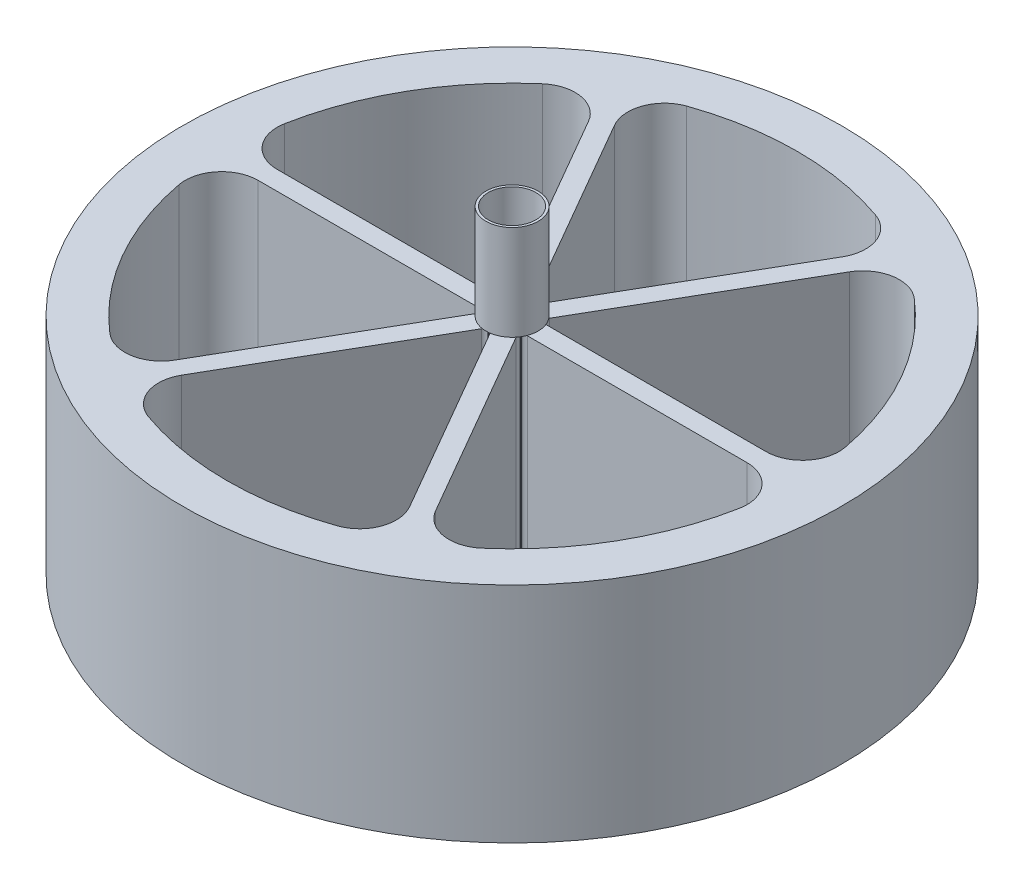
SolidWorks part; units mm, degrees
ref_plane "Front Plane" through (0, 0, 0) normal (0, 0, 1) x (1, 0, 0)
ref_plane "Top Plane" through (0, 0, 0) normal (0, 1, 0) x (1, 0, 0)
ref_plane "Right Plane" through (0, 0, 0) normal (1, 0, 0) x (0, 0, -1)
sketch "Sketch1" plane through (0, 0, 0) normal (0, 1, 0) x (1, 0, 0)
  circle A0 centre (0, 0) radius 2.75
  circle A1 centre (0, 0) radius 2.5
  dimension "D1" = 5.5
  dimension "D2" = 5
extrude "Boss-Extrude1" add sketch "Sketch1" along normal blind 10
sketch "Sketch2" plane through (0, 0, 0) normal (0, -1, 0) x (-1, 0, 0)
  line L1 (2.614, 1) -> (25.708, 1)
  line L2 (20.4475, 0) -> (20.4475, 1)
  line L3 (2.614, -1) -> (25.708, -1)
  line L4 (0.4409, -2.7637) -> (11.988, -22.7638)
  line L5 (2.173, -1.7637) -> (13.72, -21.7638)
  line L6 (-2.173, -1.7637) -> (-13.72, -21.7638)
  line L7 (-0.4409, -2.7637) -> (-11.988, -22.7638)
  line L8 (-2.614, 1) -> (-25.708, 1)
  line L9 (-2.614, -1) -> (-25.708, -1)
  line L10 (-0.4409, 2.7637) -> (-11.988, 22.7638)
  line L11 (-2.173, 1.7637) -> (-13.72, 21.7638)
  line L12 (2.173, 1.7637) -> (13.72, 21.7638)
  line L13 (0.4409, 2.7637) -> (11.988, 22.7638)
  line L14 (0.0941, -2.5116) -> (0.0272, -2.4999)
  line L15 (-0.0941, -2.5116) -> (-0.052, -2.4995)
  line L16 (2.2222, -1.1743) -> (2.1785, -1.2264)
  line L17 (2.128, -1.3373) -> (2.1386, -1.2947)
  line L18 (2.128, 1.3373) -> (2.1514, 1.2734)
  line L19 (2.2222, 1.1743) -> (2.1906, 1.2047)
  line L20 (-0.0941, 2.5116) -> (-0.0272, 2.4999)
  line L21 (0.0941, 2.5116) -> (0.052, 2.4995)
  line L22 (-2.2222, 1.1743) -> (-2.1785, 1.2264)
  line L23 (-2.128, 1.3373) -> (-2.1386, 1.2947)
  line L24 (-2.128, -1.3373) -> (-2.1514, -1.2734)
  line L25 (-2.2222, -1.1743) -> (-2.1906, -1.2047)
  arc A0 (9.9338, -28.3076) -> (19.5482, -22.7567) centre (0, 0) ccw
  arc A1 (25.708, 1) -> (29.482, 5.5509) centre (25.708, 4.8403) ccw
  circle A2 centre (0, 0) radius 2.5 construction
  arc A3 (2.2222, 1.1743) -> (2.614, 1) centre (2.614, 1.5276) ccw
  arc A4 (0.0272, -2.4999) -> (2.1386, -1.2947) centre (0, 0) ccw
  arc A5 (2.2222, -1.1743) -> (2.614, -1) centre (2.614, -1.5276) cw
  arc A6 (25.708, -1) -> (29.482, -5.5509) centre (25.708, -4.8403) cw
  arc A7 (2.128, -1.3373) -> (2.173, -1.7637) centre (2.6299, -1.5) ccw
  arc A8 (0.0941, -2.5116) -> (0.4409, -2.7637) centre (-0.0159, -3.0275) cw
  arc A9 (11.988, -22.7638) -> (9.9338, -28.3076) centre (8.6621, -24.6839) cw
  arc A10 (13.72, -21.7638) -> (19.5482, -22.7567) centre (17.0458, -19.8436) ccw
  arc A11 (-0.0941, -2.5116) -> (-0.4409, -2.7637) centre (0.0159, -3.0275) ccw
  arc A12 (-2.128, -1.3373) -> (-2.173, -1.7637) centre (-2.6299, -1.5) cw
  arc A13 (-13.72, -21.7638) -> (-19.5482, -22.7567) centre (-17.0458, -19.8436) cw
  arc A14 (-11.988, -22.7638) -> (-9.9338, -28.3076) centre (-8.6621, -24.6839) ccw
  arc A15 (-2.2222, -1.1743) -> (-2.614, -1) centre (-2.614, -1.5276) ccw
  arc A16 (-2.2222, 1.1743) -> (-2.614, 1) centre (-2.614, 1.5276) cw
  arc A17 (-25.708, 1) -> (-29.482, 5.5509) centre (-25.708, 4.8403) cw
  arc A18 (-25.708, -1) -> (-29.482, -5.5509) centre (-25.708, -4.8403) ccw
  arc A19 (-2.128, 1.3373) -> (-2.173, 1.7637) centre (-2.6299, 1.5) ccw
  arc A20 (-0.0941, 2.5116) -> (-0.4409, 2.7637) centre (0.0159, 3.0275) cw
  arc A21 (-11.988, 22.7638) -> (-9.9338, 28.3076) centre (-8.6621, 24.6839) cw
  arc A22 (-13.72, 21.7638) -> (-19.5482, 22.7567) centre (-17.0458, 19.8436) ccw
  arc A23 (0.0941, 2.5116) -> (0.4409, 2.7637) centre (-0.0159, 3.0275) ccw
  arc A24 (2.128, 1.3373) -> (2.173, 1.7637) centre (2.6299, 1.5) cw
  arc A25 (13.72, 21.7638) -> (19.5482, 22.7567) centre (17.0458, 19.8436) cw
  arc A26 (11.988, 22.7638) -> (9.9338, 28.3076) centre (8.6621, 24.6839) ccw
  arc A27 (-19.5482, -22.7567) -> (-9.9338, -28.3076) centre (0, 0) ccw
  arc A28 (-29.482, 5.5509) -> (-29.482, -5.5509) centre (0, 0) ccw
  arc A29 (-9.9338, 28.3076) -> (-19.5482, 22.7567) centre (0, 0) ccw
  arc A30 (19.5482, 22.7567) -> (9.9338, 28.3076) centre (0, 0) ccw
  arc A31 (29.482, -5.5509) -> (29.482, 5.5509) centre (0, 0) ccw
  arc A32 (-2.1514, -1.2734) -> (-0.052, -2.4995) centre (0, 0) ccw
  arc A33 (-2.1785, 1.2264) -> (-2.1906, -1.2047) centre (0, 0) ccw
  arc A34 (-0.0272, 2.4999) -> (-2.1386, 1.2947) centre (0, 0) ccw
  arc A35 (2.1514, 1.2734) -> (0.052, 2.4995) centre (0, 0) ccw
  arc A36 (2.1785, -1.2264) -> (2.1906, 1.2047) centre (0, 0) ccw
  point P85 (0, 0)
  point P108 (0, 0)
  dimension "D1" = 60
  dimension "D4" = 6
extrude "Boss-Extrude3" add sketch "Sketch2" along normal blind 23.5 separate body contours L6 A13 A27 A14 L7 A11 L15 A32 L24 A12 | L4 A9 A0 A10 L5 A7 L17 A4 L14 A8 | L1 A1 A31 A6 L3 A5 L16 A36 L19 A3 | L13 A26 A30 A25 L12 A24 L18 A35 L21 A23 | L11 A22 A29 A21 L10 A20 L20 A34 L23 A19 | L9 A18 A28 A17 L8 A16 L22 A33 L25 A15
sketch "Sketch5" plane through (0, -23.5, 0) normal (0, -1, 0) x (-1, 0, 0)
  circle A0 centre (0, 0) radius 30
  circle A1 centre (0, 0) radius 34.6666
extrude "Boss-Extrude4" add sketch "Sketch5" against normal blind 23.5
sketch "Sketch6" plane through (0, 10, 0) normal (0, 1, 0) x (1, 0, 0)
  circle A0 centre (0, 0) radius 1.5
extrude "Boss-Extrude5" add sketch "Sketch6" against normal blind 28
sketch "Sketch7" plane through (0, 10, 0) normal (0, 1, 0) x (1, 0, 0)
  circle A0 centre (0, 0) radius 2.25
  dimension "D1" = 4.5
extrude "Cut-Extrude1" cut sketch "Sketch7" against normal blind 28
